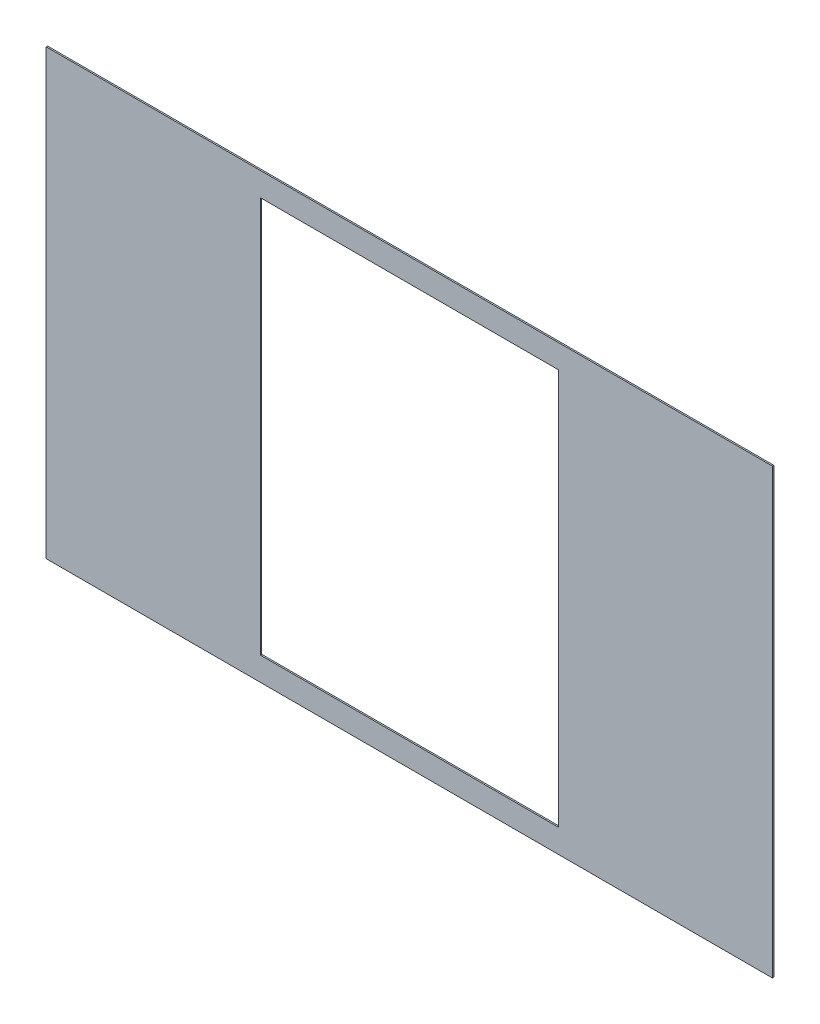
SolidWorks part; units mm, degrees
ref_plane "Front Plane" through (0, 0, 0) normal (0, 0, 1) x (1, 0, 0)
ref_plane "Top Plane" through (0, 0, 0) normal (0, 1, 0) x (1, 0, 0)
ref_plane "Right Plane" through (0, 0, 0) normal (1, 0, 0) x (0, 0, -1)
sketch "Sketch1" plane through (0, 0, 0) normal (0, 0, 1) x (1, 0, 0)
  line L1 (385, 235) -> (-385, 235)
  line L2 (385, 235) -> (385, -235)
  line L3 (385, -235) -> (-385, -235)
  line L4 (-385, 235) -> (-385, -235)
  line L5 (385, 235) -> (-385, -235) construction
  line L6 (385, -235) -> (-385, 235) construction
  point P0 (0, 0)
  dimension "D1" = 770
  dimension "D2" = 470
extrude "Boss-Extrude1" add sketch "Sketch1" along normal blind 1.5
sketch "Sketch3" plane through (0, 0, 1.5) normal (0, 0, 1) x (1, 0, 0)
  line L1 (158, 210) -> (-158, 210)
  line L2 (158, 210) -> (158, -210)
  line L3 (158, -210) -> (-158, -210)
  line L4 (-158, 210) -> (-158, -210)
  line L5 (158, 210) -> (-158, -210) construction
  line L6 (158, -210) -> (-158, 210) construction
  point P0 (0, 0)
  dimension "D1" = 420
  dimension "D2" = 316
extrude "Cut-Extrude4" cut sketch "Sketch3" along normal blind 17 and the other way blind 10
